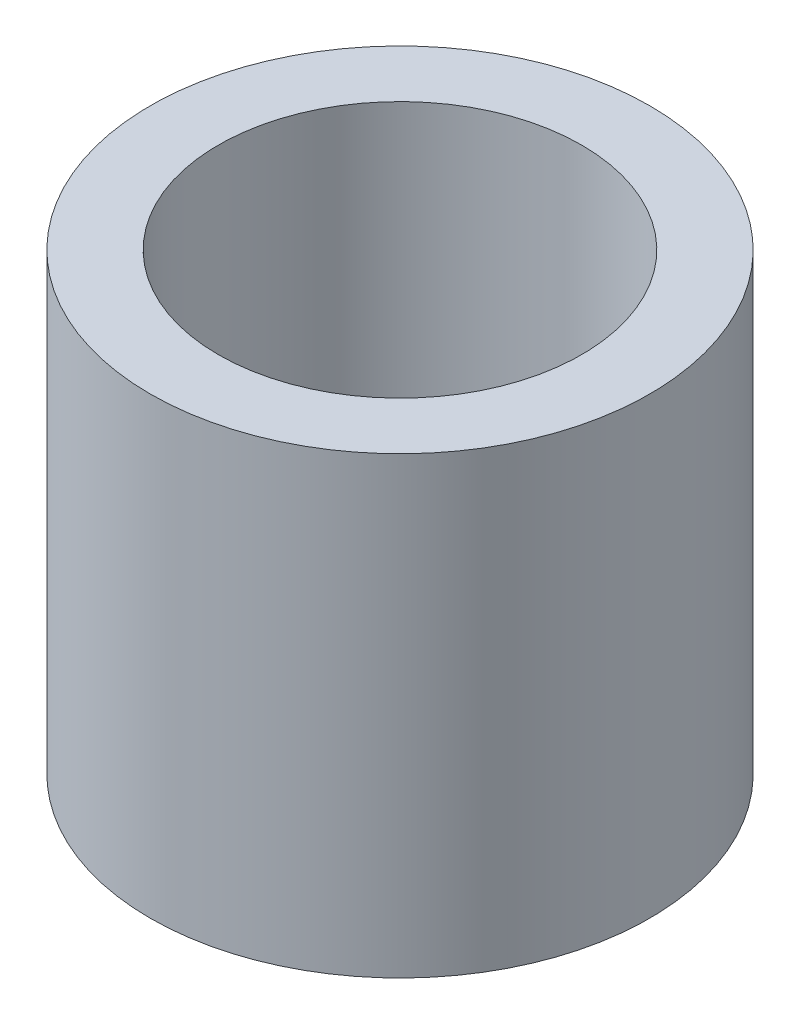
SolidWorks part; units mm, degrees
ref_plane "Front Plane" through (0, 0, 0) normal (0, 0, 1) x (1, 0, 0)
ref_plane "Top Plane" through (0, 0, 0) normal (0, 1, 0) x (1, 0, 0)
ref_plane "Right Plane" through (0, 0, 0) normal (1, 0, 0) x (0, 0, -1)
sketch "Sketch1" plane through (0, 0, 0) normal (0, 1, 0) x (1, 0, 0)
  circle A0 centre (0, 0) radius 5.5
  circle A1 centre (0, 0) radius 4
  dimension "D1" = 11
  dimension "D2" = 8
extrude "Boss-Extrude1" add sketch "Sketch1" along normal blind 10
